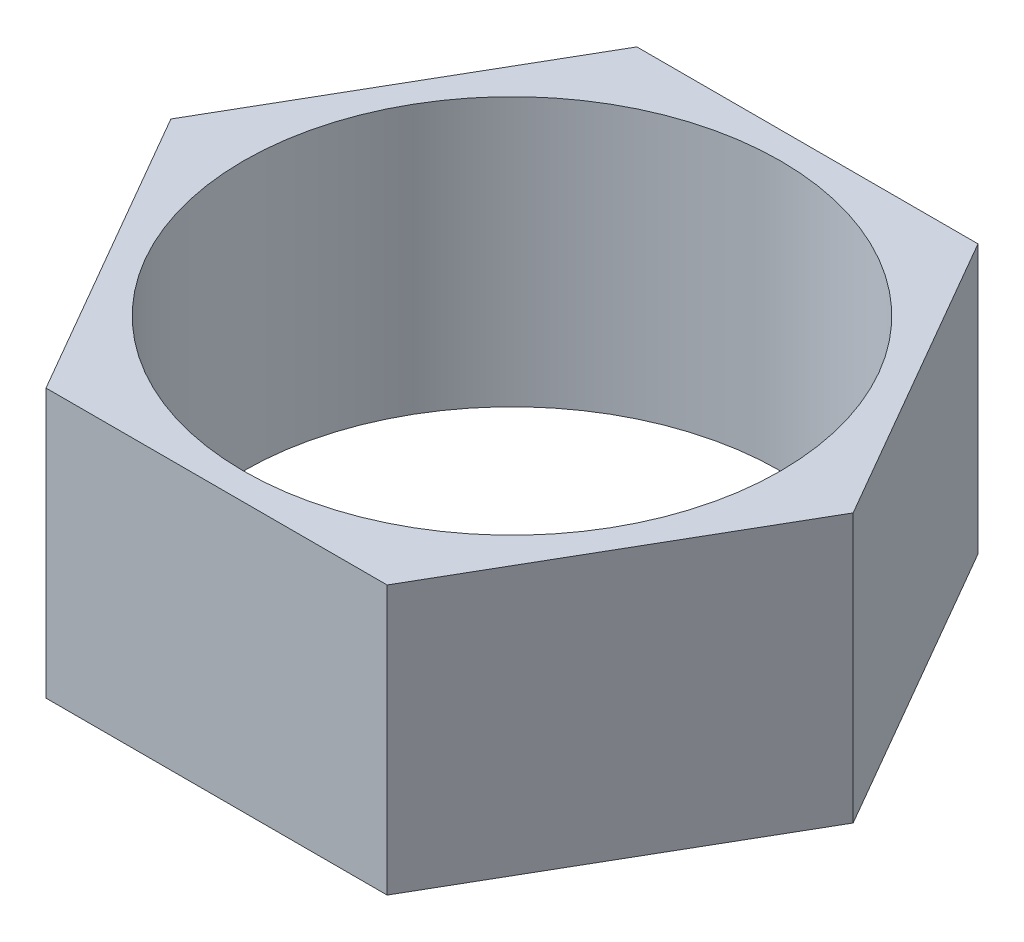
SolidWorks part; units mm, degrees
ref_plane "Front Plane" through (0, 0, 0) normal (0, 0, 1) x (1, 0, 0)
ref_plane "Top Plane" through (0, 0, 0) normal (0, 1, 0) x (1, 0, 0)
ref_plane "Right Plane" through (0, 0, 0) normal (1, 0, 0) x (0, 0, -1)
sketch "Sketch1" plane through (0, 0, 0) normal (0, 1, 0) x (1, 0, 0)
  line L1 (12.7017, 0) -> (6.3509, 11)
  line L2 (6.3509, 11) -> (-6.3509, 11)
  line L3 (-6.3509, 11) -> (-12.7017, 0)
  line L4 (-12.7017, 0) -> (-6.3509, -11)
  line L5 (-6.3509, -11) -> (6.3509, -11)
  line L6 (6.3509, -11) -> (12.7017, 0)
  circle A0 centre (0, 0) radius 10
  circle A1 centre (0, 0) radius 11 construction
  dimension "D1" = 11
  dimension "D2" = 11
extrude "Boss-Extrude2" add sketch "Sketch1" along normal blind 10
